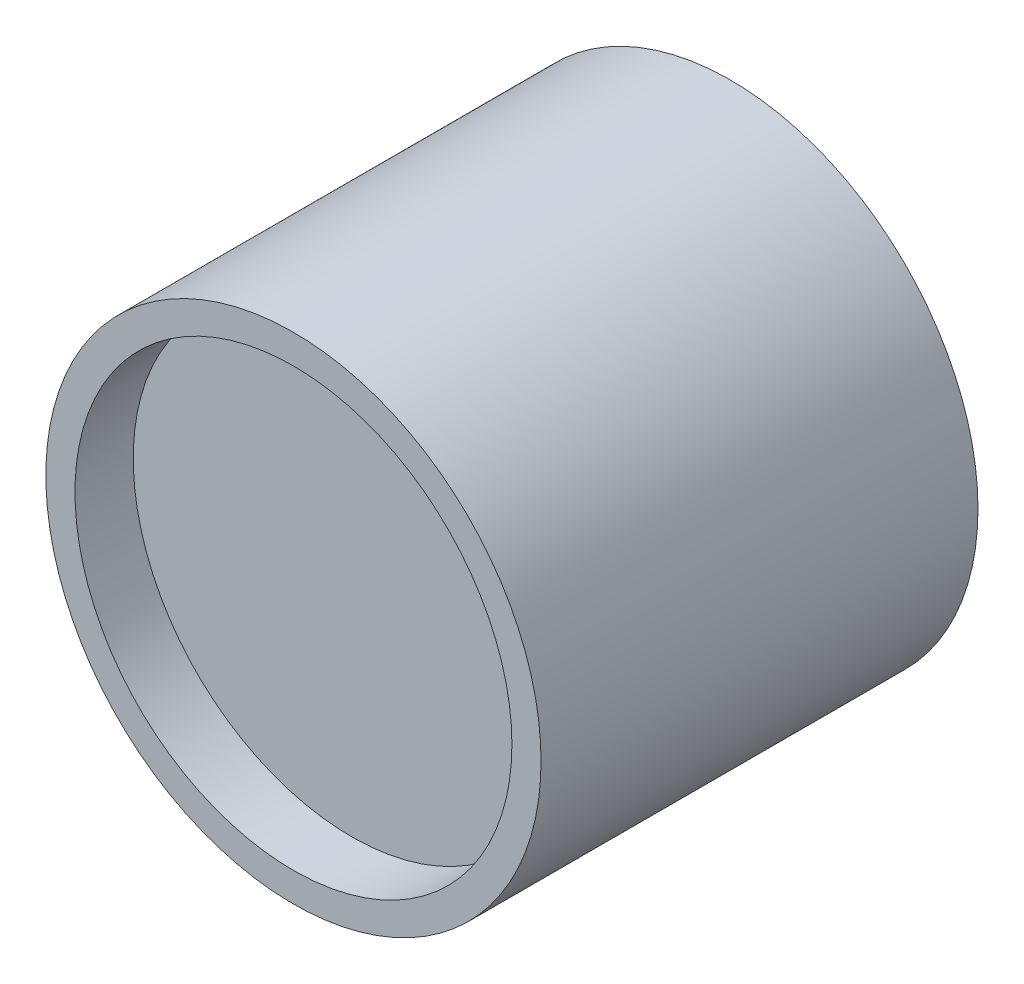
SolidWorks part; units mm, degrees
material "Plain Carbon Steel"
ref_plane "Front Plane" through (0, 0, 0) normal (0, 0, 1) x (1, 0, 0)
ref_plane "Top Plane" through (0, 0, 0) normal (0, 1, 0) x (1, 0, 0)
ref_plane "Right Plane" through (0, 0, 0) normal (1, 0, 0) x (0, 0, -1)
sketch "Sketch1" plane through (0, 0, 0) normal (0, 0, 1) x (1, 0, 0)
  circle A0 centre (0, 0) radius 42.5
  dimension "D1" = 85
extrude "Boss-Extrude1" add sketch "Sketch1" along normal blind 75
sketch "Sketch2" plane through (0, 0, 75) normal (0, 0, 1) x (1, 0, 0)
  circle A0 centre (0, 0) radius 37.5
  dimension "D1" = 75
extrude "Cut-Extrude1" cut sketch "Sketch2" against normal blind 10 contours A0
sketch "Sketch3" plane through (0, 0, 0) normal (0, 0, -1) x (-1, 0, 0)
  circle A0 centre (0, 0) radius 37.5
  dimension "D1" = 75
extrude "Cut-Extrude2" cut sketch "Sketch3" against normal blind 10
